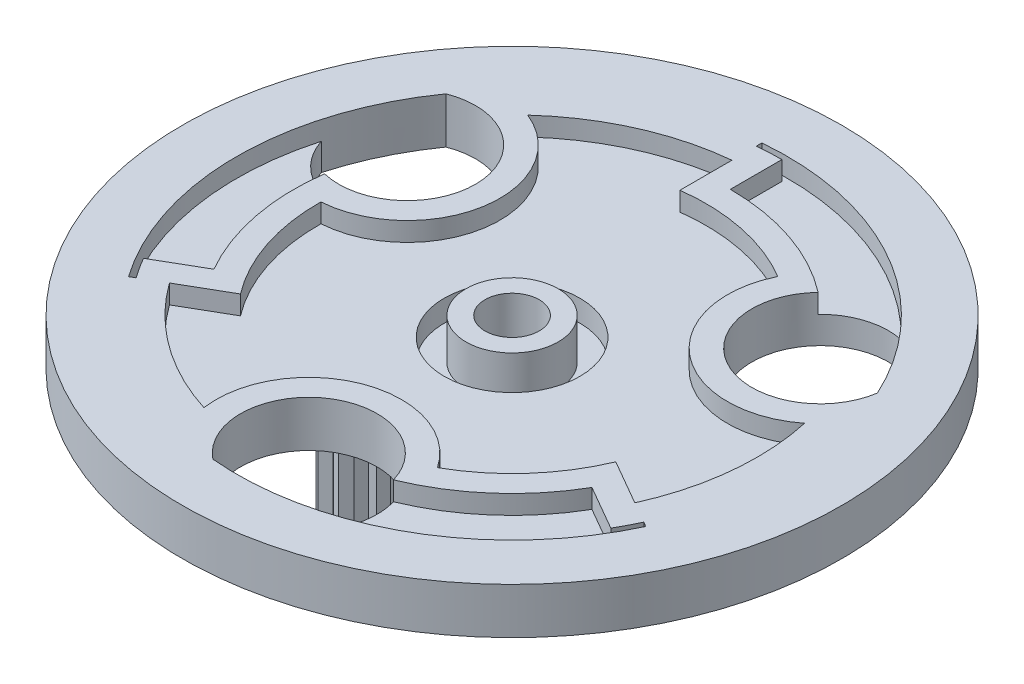
SolidWorks part; units mm, degrees
ref_plane "Front Plane" through (0, 0, 0) normal (0, 0, 1) x (1, 0, 0)
ref_plane "Top Plane" through (0, 0, 0) normal (0, 1, 0) x (1, 0, 0)
ref_plane "Right Plane" through (0, 0, 0) normal (1, 0, 0) x (0, 0, -1)
sketch "Sketch1" plane through (0, 0, 0) normal (0, 0, 1) x (1, 0, 0)
  line L0 (0, -4.9186) -> (0, 6.1744) construction
  line L1 (1, -3.75) -> (1, 3.75)
  line L2 (1, 3.75) -> (1.7, 3.75)
  line L3 (1.7, 3.75) -> (1.7, 2.25)
  line L4 (1.7, 2.25) -> (2.5, 2.25)
  line L5 (2.5, 2.25) -> (2.5, 3.75)
  line L6 (2.5, 3.75) -> (12.15, 3.75)
  line L7 (12.15, 3.75) -> (12.15, 2.05)
  line L9 (2.2, 0.25) -> (2.2, -2.45)
  line L10 (2.2, -2.45) -> (1.9, -2.45)
  line L11 (1.9, -2.45) -> (1.9, -3.75)
  line L12 (1.9, -3.75) -> (1, -3.75)
  line L13 (2.2, 0.25) -> (3.5, 0.25)
  line L14 (3.5, 0.25) -> (3.5, -2.45)
  line L15 (3.5, -2.45) -> (4, -2.45)
  line L16 (4, -2.45) -> (4, 2.05)
  line L17 (4, 2.05) -> (12.15, 2.05)
  point P11 (3.2394, 0.9704)
  point P16 (1, 0)
  dimension "D1" = 2
  dimension "D2" = 0.7
  dimension "D3" = 0.8
  dimension "D4" = 24.3
  dimension "D5" = 1.7
  dimension "D6" = 4.4
  dimension "D7" = 3.8
  dimension "D8" = 1.5
  dimension "D9" = 7.5
  dimension "D10" = 1.3
  dimension "D11" = 0.5
  dimension "D12" = 2
  dimension "D13" = 8
revolve "Revolve1" add sketch "Sketch1" angle 360 about L0
sketch "Sketch2" plane through (0, 3.75, 0) normal (0, 1, 0) x (1, 0, 0)
  line L0 (-0.9, 9.0051) -> (-0.9, 7.089)
  line L1 (0, 9.9459) -> (0, 8.0459)
  line L2 (-0.9, 9.9051) -> (-0.9, 10.11)
  line L3 (9.0281, -4.1731) -> (9.2055, -4.2756)
  line L4 (8.6134, -4.973) -> (6.968, -4.023)
  line L5 (8.2487, -3.7231) -> (6.5893, -2.7651)
  line L6 (-8.1281, -5.732) -> (-8.3055, -5.8344)
  line L7 (-8.6134, -4.973) -> (-6.968, -4.023)
  line L8 (-7.3487, -5.282) -> (-5.6893, -4.3239)
  line L9 (-0.9, 9.9051) -> (-0.9, 9.0051) construction
  line L10 (0, 8.0459) -> (-0.9, 8.0459) construction
  line L11 (1.4587, 6.9955) -> (1.6424, 7.8765) construction
  line L12 (8.8382, 1.9463) -> (8.282, 2.6538) construction
  line L13 (3.9118, 2.6945) -> (10.006, 6.8921) construction
  line L14 (9.2152, 4.2548) -> (4.9088, 6.375) construction
  arc A0 (-6.1046, 6.681) -> (-0.9, 9.0051) centre (0, 0) cw
  arc A1 (-0.9, 7.089) -> (3.6583, 6.1385) centre (0, 0) cw
  arc A2 (3.6583, 6.1385) -> (8.8382, 1.9463) centre (6.7263, 4.633) ccw
  arc A3 (0, 8.0459) -> (4.9088, 6.375) centre (0, 0) cw
  arc A4 (4.9088, 6.375) -> (9.2152, 4.2548) centre (6.7263, 4.633) ccw
  arc A5 (0, 9.9459) -> (-0.9, 9.9051) centre (0, 0) ccw
  arc A6 (-0.9, 10.11) -> (9.2152, 4.2548) centre (0, 0) cw
  arc A7 (3.0665, -7.4387) -> (-0.9228, -10.108) centre (0.6492, -8.1416) ccw
  arc A8 (9.2055, -4.2756) -> (-0.9228, -10.108) centre (0, 0) cw
  arc A9 (8.6134, -4.973) -> (9.0281, -4.1731) centre (0, 0) ccw
  arc A10 (6.968, -4.023) -> (3.0665, -7.4387) centre (0, 0) cw
  arc A11 (8.8382, 1.9463) -> (8.2487, -3.7231) centre (0, 0) cw
  arc A12 (6.5893, -2.7651) -> (3.487, -6.2374) centre (0, 0) cw
  arc A13 (3.487, -6.2374) -> (-2.7336, -8.6273) centre (0.6492, -8.1416) ccw
  arc A14 (-7.9753, 1.0636) -> (-8.2924, 5.8532) centre (-7.3755, 3.5086) ccw
  arc A15 (-8.3055, -5.8344) -> (-8.2924, 5.8532) centre (0, 0) cw
  arc A16 (-8.6134, -4.973) -> (-8.1281, -5.732) centre (0, 0) ccw
  arc A17 (-6.968, -4.023) -> (-7.9753, 1.0636) centre (0, 0) cw
  arc A18 (-2.7336, -8.6273) -> (-7.3487, -5.282) centre (0, 0) cw
  arc A19 (-5.6893, -4.3239) -> (-7.1453, 0.0989) centre (0, 0) cw
  arc A20 (-7.1453, 0.0989) -> (-6.1046, 6.681) centre (-7.3755, 3.5086) ccw
  circle A21 centre (0, 0) radius 2.5 construction
  circle A22 centre (0, 0) radius 2.5
  circle A23 centre (0, 0) radius 12.15 construction
  point P16 (3.9118, 2.6945)
  point P41 (0, 0)
  point P48 (9.0281, 4.5074)
  dimension "D2" = 3.1
  dimension "D4" = 2
  dimension "D3" = 0.9
  dimension "D5" = 5.7
  dimension "D6" = 7.4
  dimension "D7" = 4.8
  dimension "D8" = 1.9
  dimension "D1" = 3
extrude "Cut-Extrude1" cut sketch "Sketch2" against normal blind 0.7
sketch "Sketch3" plane through (0, 3.05, 0) normal (0, 1, 0) x (1, 0, 0)
  arc A0 (9.2152, 4.2548) -> (7.26, 7.0933) centre (6.7263, 4.633) cw
  arc A1 (9.2152, 4.2548) -> (-0.9, 10.11) centre (0, 0) ccw construction
  arc A2 (4.9088, 6.375) -> (9.2152, 4.2548) centre (6.7263, 4.633) ccw construction
  arc A3 (7.26, 7.0933) -> (9.2177, 4.2493) centre (0, 0) cw
  arc M4 (4.9088, 6.375) -> (9.2152, 4.2548) centre (6.7263, 4.633) ccw
  arc M5 (9.2152, 4.2548) -> (-0.9, 10.11) centre (0, 0) ccw
extrude "Cut-Extrude2" cut sketch "Sketch3" against normal blind 1 contours A0 M4 M5
pattern_circular "CirPattern1" count 3 over 360 about axis through (0, -4.9186, 0) along (0, -1, 0) of "Cut-Extrude2"
sketch "Sketch5" plane through (0, 2.05, 0) normal (0, -1, 0) x (1, 0, 0)
  line L0 (-0.3, 3.9887) -> (-0.3, 4.777)
  line L1 (-0.3, 4.777) -> (-0.15, 5.1478)
  line L2 (0.3, 3.9887) -> (0.3, 4.777)
  line L3 (0.3, 4.777) -> (0.15, 5.1478)
  line L4 (0, -0.4706) -> (0, 7.009) construction
  circle A0 centre (0, 0) radius 4 construction
  arc A1 (-0.3, 3.9887) -> (0.3, 3.9887) centre (0, 0) cw
  arc A2 (-0.15, 5.1478) -> (0.15, 5.1478) centre (0, 0) cw
  point P12 (0, 4)
  point P13 (0, 5.15)
  point P14 (-0.2014, 5.1461)
  dimension "D1" = 5.15
  dimension "D2" = 0.6
  dimension "D3" = 0.4
  dimension "D4" = 0.3
extrude "Boss-Extrude1" add sketch "Sketch5" along normal up to surface (4.5 mm away) up to face at (0, -2.45, -4)
pattern_circular "CirPattern2" count 20 over 360 about axis through (0, 0, 0) along (0, 1, 0) of "Boss-Extrude1"
